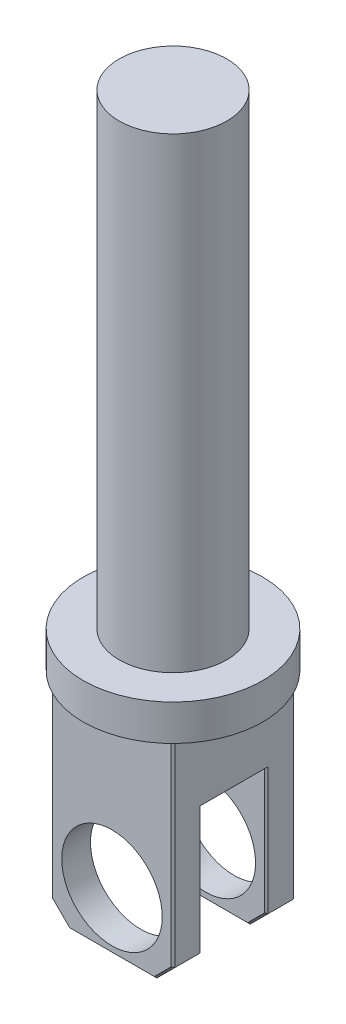
SolidWorks part; units mm, degrees
material "Plain Carbon Steel"
ref_plane "Front Plane" through (0, 0, 0) normal (0, 0, 1) x (1, 0, 0)
ref_plane "Top Plane" through (0, 0, 0) normal (0, 1, 0) x (1, 0, 0)
ref_plane "Right Plane" through (0, 0, 0) normal (1, 0, 0) x (0, 0, -1)
sketch "Sketch1" plane through (0, 0, 0) normal (0, 1, 0) x (1, 0, 0)
  circle A0 centre (0, 0) radius 12.5
  dimension "D1" = 25
extrude "Boss-Extrude1" add sketch "Sketch1" along normal mid plane 100
sketch "Sketch2" plane through (0, 0, 0) normal (0, 0, 1) x (1, 0, 0)
  line L0 (-12.5, -50) -> (12.5, -50) construction
  circle A0 centre (0, -42) radius 7
  point P4 (0, 0)
  dimension "D1" = 14
  dimension "D2" = 8
extrude "Cut-Extrude1" cut sketch "Sketch2" against normal up to next and the other way up to next
sketch "Sketch3" plane through (0, 0, 0) normal (1, 0, 0) x (0, 0, -1)
  line L0 (-12.5, -50) -> (12.5, -50) construction
  line L1 (-4.5, -50) -> (4.5, -50)
  line L2 (-4.5, -50) -> (-4.5, -30)
  line L3 (-4.5, -30) -> (4.5, -30)
  line L4 (4.5, -50) -> (4.5, -30)
  line L5 (-11.7607, -40.3332) -> (12.3638, -40.3332) construction
  point P8 (0, -30)
  point P10 (0, 0)
  dimension "D1" = 9
  dimension "D2" = 5
extrude "Cut-Extrude2" cut sketch "Sketch3" against normal up to next and the other way up to next
sketch "Sketch4" plane through (0, -50, 0) normal (0, -1, 0) x (1, 0, 0)
  line L1 (-8.5, -8.5) -> (8.5, -8.5)
  line L2 (-8.5, -8.5) -> (-8.5, 8.5)
  line L3 (-8.5, 8.5) -> (8.5, 8.5)
  line L4 (8.5, -8.5) -> (8.5, 8.5)
  line L5 (-8.5, -8.5) -> (8.5, 8.5) construction
  line L6 (-8.5, 8.5) -> (8.5, -8.5) construction
  point P0 (0, 0)
  dimension "D1" = 17
extrude "Cut-Extrude4" cut sketch "Sketch4" against normal blind 30 flip side to cut
sketch "Sketch5" plane through (0, 50, 0) normal (0, 1, 0) x (1, 0, 0)
  circle A0 centre (0, 0) radius 7.5
  circle A1 centre (0, 0) radius 12.5 construction
  circle A2 centre (0, 0) radius 12.5
  dimension "D1" = 15
extrude "Cut-Extrude5" cut sketch "Sketch5" along direction (0, -1, 0) on the side against the normal up to surface (70 mm away)
chamfer "Chamfer2" distance 2.5 angle 45 4 edges at (8.5, -50, -6.5) (8.5, -50, 6.5) (-8.5, -50, 6.5) (-8.5, -50, -6.5)
chamfer "Chamfer1" distance 0.25 angle 45 26 edges at (8.5, -33.75, 8.5) (-8.5, -33.75, 8.5) (-8.5, -33.75, -8.5) (8.5, -33.75, -8.5) (0, -20, 8.5) (-8.5, -20, 0) (0, -20, -8.5) (8.5, -20, 0) (8.5, -30, 0) (8.5, -38.75, -4.5) (8.5, -38.75, 4.5) (0, -50, 8.5) (0, -50, 4.5) (0, -50, -4.5) (0, -50, -8.5) (-8.5, -38.75, -4.5) (-8.5, -30, 0) (-8.5, -38.75, 4.5) (7.25, -48.75, -4.5) (7.25, -48.75, 4.5) (-7.25, -48.75, 4.5) (-7.25, -48.75, -4.5) (7.25, -48.75, -8.5) (7.25, -48.75, 8.5) (-7.25, -48.75, 8.5) (-7.25, -48.75, -8.5)
sketch "Sketch7" plane through (0, -20, 0) normal (0, 1, 0) x (1, 0, 0)
  circle A0 centre (0, 0) radius 12.5
  dimension "D1" = 25
extrude "Boss-Extrude2" add sketch "Sketch7" along normal blind 5
